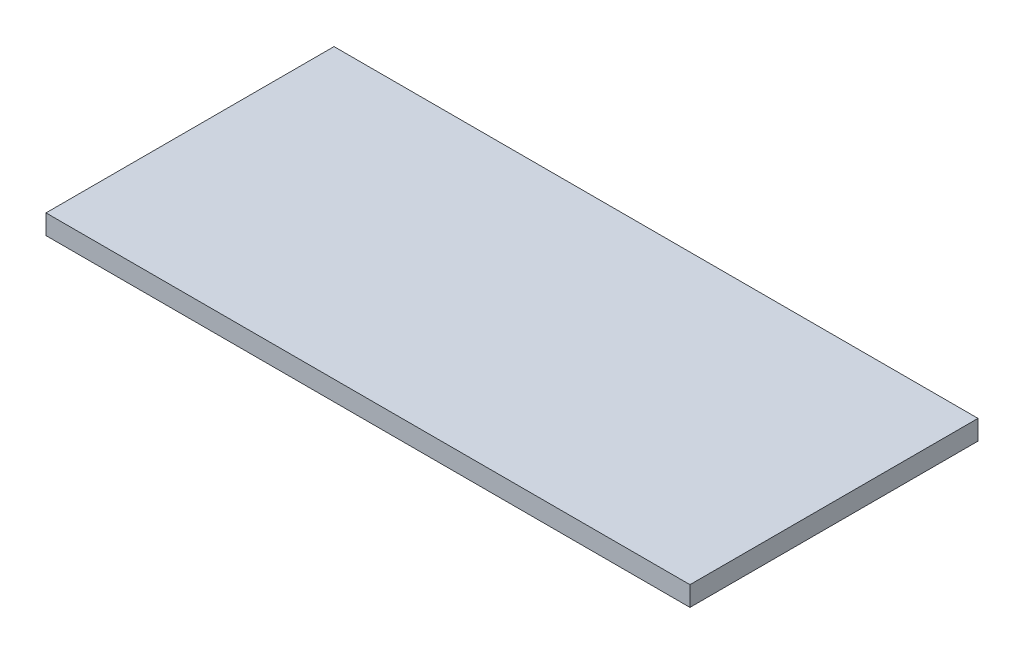
SolidWorks part; units mm, degrees
material "Teak"
ref_plane "Front Plane" through (0, 0, 0) normal (0, 0, 1) x (1, 0, 0)
ref_plane "Top Plane" through (0, 0, 0) normal (0, 1, 0) x (1, 0, 0)
ref_plane "Right Plane" through (0, 0, 0) normal (1, 0, 0) x (0, 0, -1)
sketch "Sketch1" plane through (0, 0, 0) normal (0, 1, 0) x (1, 0, 0)
  line L1 (0, 0) -> (588, 0)
  line L2 (0, 0) -> (0, 263)
  line L3 (0, 263) -> (588, 263)
  line L4 (588, 0) -> (588, 263)
  dimension "D1" = 263
  dimension "D2" = 588
extrude "Boss-Extrude1" add sketch "Sketch1" along normal blind 18
